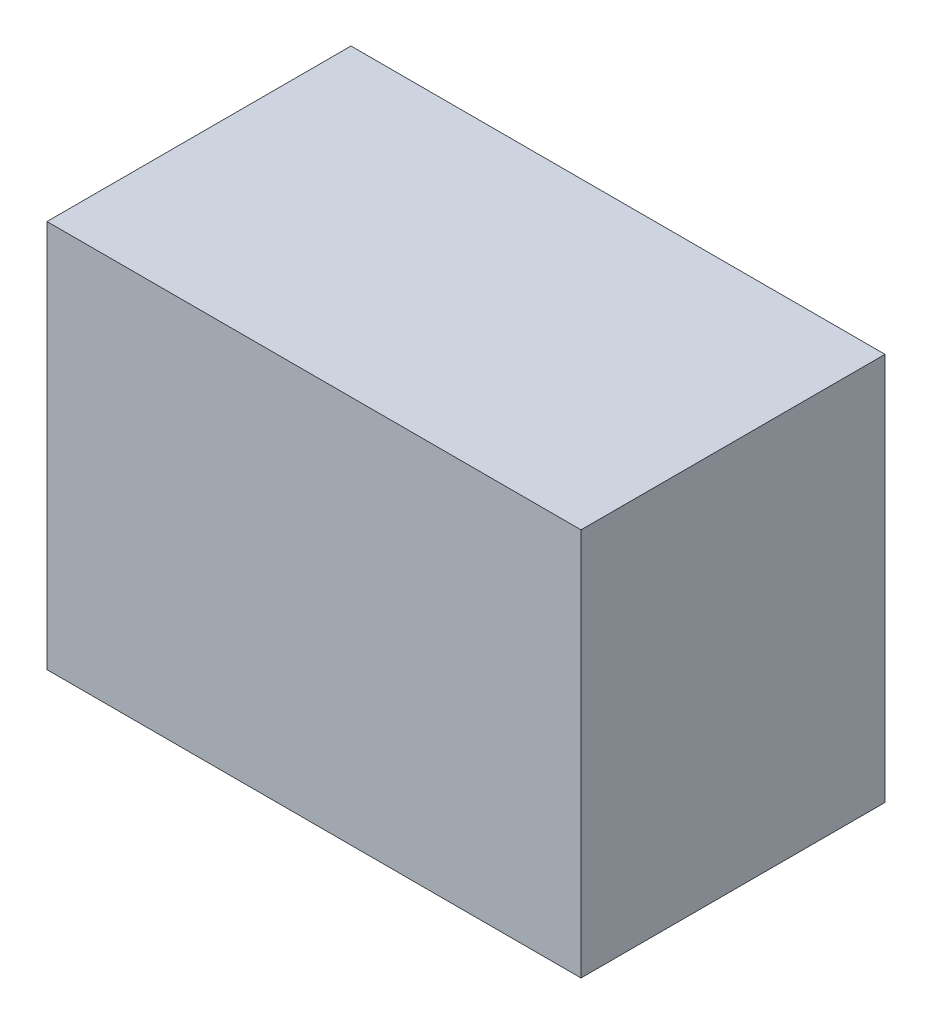
SolidWorks part; units mm, degrees
ref_plane "Front Plane" through (0, 0, 0) normal (0, 0, 1) x (1, 0, 0)
ref_plane "Top Plane" through (0, 0, 0) normal (0, 1, 0) x (1, 0, 0)
ref_plane "Right Plane" through (0, 0, 0) normal (1, 0, 0) x (0, 0, -1)
sketch "Sketch1" plane through (0, 0, 0) normal (0, 0, 1) x (1, 0, 0)
  line L1 (-26.35, -19.15) -> (26.35, -19.15)
  line L2 (-26.35, -19.15) -> (-26.35, 19.15)
  line L3 (-26.35, 19.15) -> (26.35, 19.15)
  line L4 (26.35, -19.15) -> (26.35, 19.15)
  line L5 (-26.35, -19.15) -> (26.35, 19.15) construction
  line L6 (-26.35, 19.15) -> (26.35, -19.15) construction
  point P0 (0, 0)
extrude "Envelope" add sketch "Sketch1" along normal blind 30
